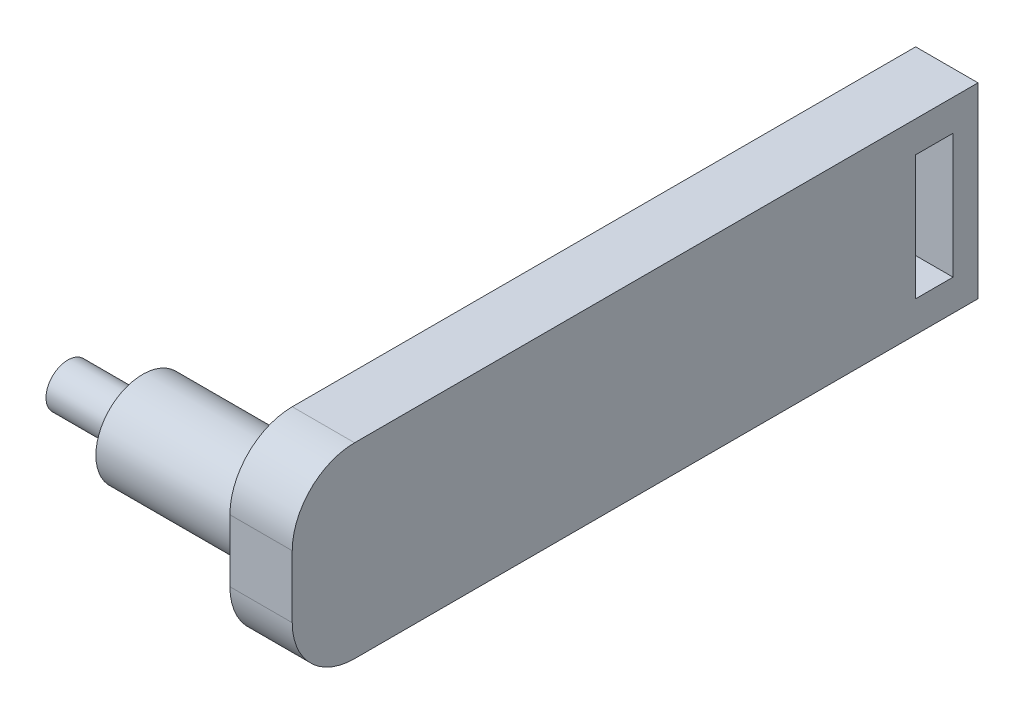
SolidWorks part; units mm, degrees
ref_plane "Front Plane" through (0, 0, 0) normal (0, 0, 1) x (1, 0, 0)
ref_plane "Top Plane" through (0, 0, 0) normal (0, 1, 0) x (1, 0, 0)
ref_plane "Right Plane" through (0, 0, 0) normal (1, 0, 0) x (0, 0, -1)
sketch "Sketch1" plane through (0, 0, 0) normal (0, 1, 0) x (1, 0, 0)
  line L1 (-61.8805, -26.2097) -> (-56.8805, -26.2097)
  line L2 (-61.8805, -26.2097) -> (-61.8805, 28.7903)
  line L3 (-61.8805, 28.7903) -> (-56.8805, 28.7903)
  line L4 (-56.8805, -26.2097) -> (-56.8805, 28.7903)
  line L6 (-56.8805, 28.7903) -> (-56.8805, 23.7903)
  dimension "D5" = 5
extrude "Boss-Extrude1" add sketch "Sketch1" along normal blind 15 contours L1 L4 L3 L2
sketch "Sketch2" plane through (-61.8805, 0, 0) normal (-1, 0, 0) x (0, 0, 1)
  line L2 (26.2097, 0) -> (-28.7903, 0) construction
  line L3 (-28.7903, 15) -> (-28.7903, 0) construction
  line L5 (-26.7903, 2.5) -> (-23.7903, 2.5)
  line L6 (-26.7903, 2.5) -> (-26.7903, 12.5)
  line L7 (-26.7903, 12.5) -> (-23.7903, 12.5)
  line L8 (-23.7903, 2.5) -> (-23.7903, 12.5)
  dimension "D4" = 2.5
  dimension "D5" = 10
  dimension "D6" = 2
  dimension "D7" = 3
fillet "Fillet1" radius 5 2 edges at (-59.3805, 15, 26.2097) (-59.3805, 0, 26.2097)
sketch "Sketch3" plane through (-61.8805, 0, 0) normal (-1, 0, 0) x (0, 0, 1)
  line L3 (21.2097, 15) -> (-28.7903, 15) construction
  line L4 (26.2097, 10) -> (26.2097, 5) construction
  circle A1 centre (21.2097, 7.5) radius 3.75
  dimension "D1" = 7.5
  dimension "D2" = 5
  dimension "D3" = 7.5
extrude "Cut-Extrude1" cut sketch "Sketch2" against normal up to surface (5 mm away) up to face at (-56.8805, 7.5, 6.5549)
extrude "Boss-Extrude2" add sketch "Sketch3" along normal blind 12
sketch "Sketch4" plane through (-73.8805, 0, 0) normal (-1, 0, 0) x (0, 0, 1)
  circle A0 centre (21.2097, 7.5) radius 2.9
  circle A1 centre (21.2097, 7.5) radius 1.75
extrude "Boss-Extrude3" add sketch "Sketch4" along normal blind 6 contours A1
